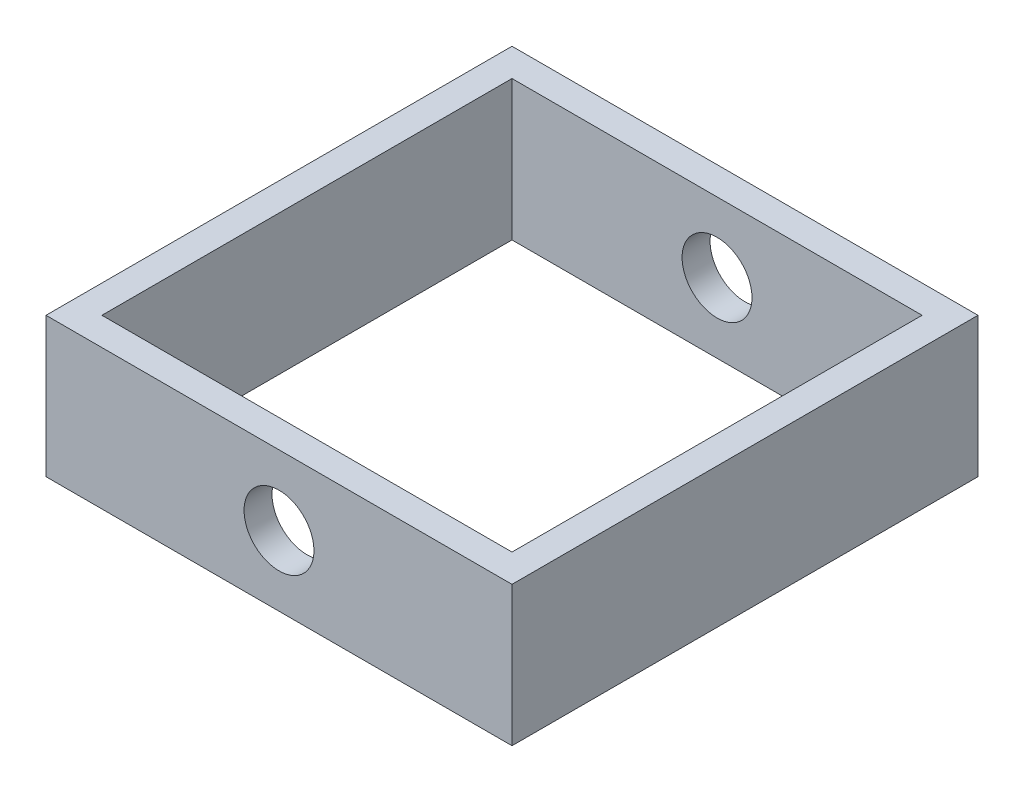
SolidWorks part; units mm, degrees
ref_plane "Front Plane" through (0, 0, 0) normal (0, 0, 1) x (1, 0, 0)
ref_plane "Top Plane" through (0, 0, 0) normal (0, 1, 0) x (1, 0, 0)
ref_plane "Right Plane" through (0, 0, 0) normal (1, 0, 0) x (0, 0, -1)
sketch "Sketch1" plane through (0, 0, 0) normal (0, 1, 0) x (1, 0, 0)
  line L0 (6, 6) -> (6, 94)
  line L1 (0, 0) -> (100, 0)
  line L2 (0, 0) -> (0, 100)
  line L3 (0, 100) -> (100, 100)
  line L4 (100, 0) -> (100, 100)
  line L5 (6, 94) -> (94, 94)
  line L6 (94, 6) -> (94, 94)
  line L7 (6, 6) -> (94, 6)
  dimension "D1" = 100
  dimension "D2" = 100
  dimension "D3" = 6
extrude "Boss-Extrude1" add sketch "Sketch1" along normal blind 30
sketch "Sketch2" plane through (0, 0, 0) normal (0, 0, 1) x (1, 0, 0)
  line L0 (50, 30) -> (50, 0) construction
  line L1 (0, 30) -> (100, 30) construction
  line L2 (0, 0) -> (100, 0) construction
  line L3 (100, 15) -> (0, 15) construction
  line L4 (100, 30) -> (100, 0) construction
  line L5 (0, 30) -> (0, 0) construction
  circle A0 centre (50, 15) radius 7.5
  dimension "D1" = 15
extrude "Cut-Extrude1" cut sketch "Sketch2" against normal through all
